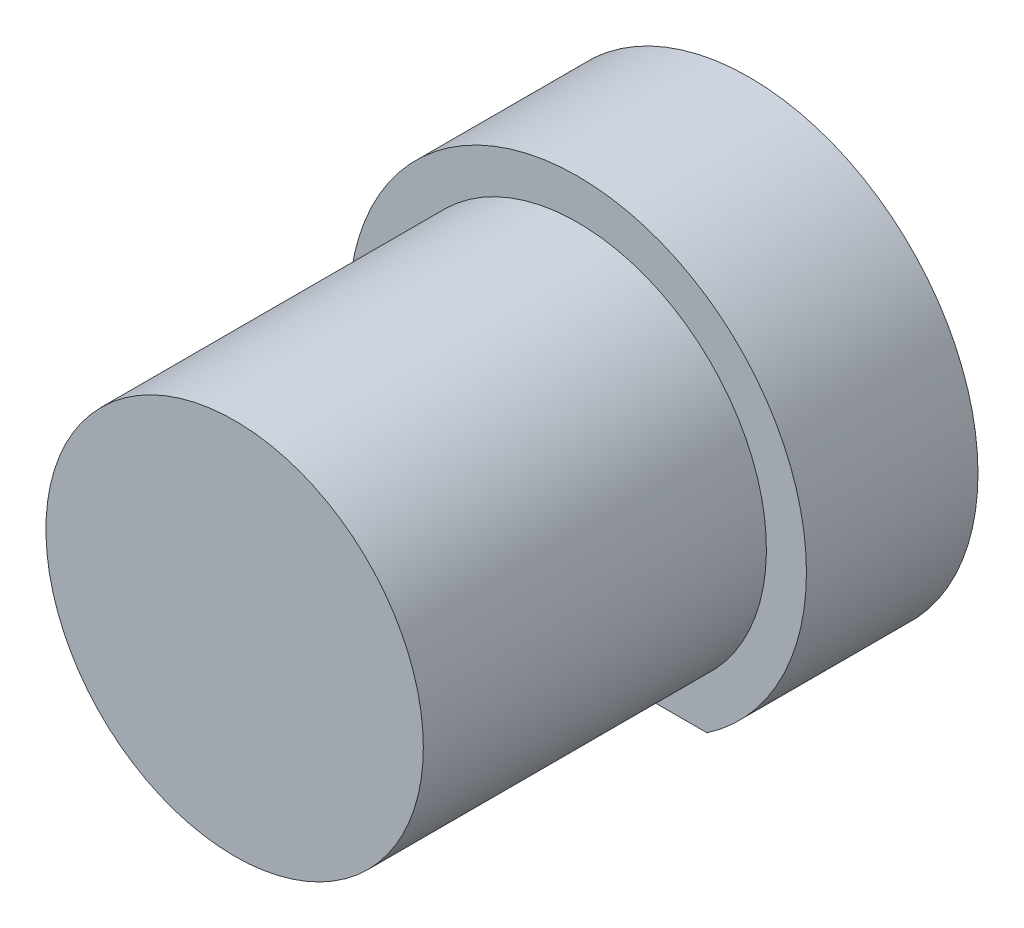
SolidWorks part; units mm, degrees
ref_plane "Front" through (0, 0, 0) normal (0, 0, 1) x (1, 0, 0)
ref_plane "Top" through (0, 0, 0) normal (0, 1, 0) x (1, 0, 0)
ref_plane "Right" through (0, 0, 0) normal (1, 0, 0) x (0, 0, -1)
sketch "Sketch1" plane through (0, 0, 0) normal (0, 0, 1) x (1, 0, 0)
  circle A0 centre (0, 0) radius 2
  dimension "D1" = 4
extrude "Boss-Extrude1" add sketch "Sketch1" along normal blind 1.5
sketch "Sketch2" plane through (0, 0, 1.5) normal (0, 0, 1) x (1, 0, 0)
  circle A0 centre (0, 0) radius 1.65
  dimension "D1" = 3.3
extrude "Boss-Extrude2" add sketch "Sketch2" along normal blind 3
sketch "Sketch3" plane through (0, 0, 1.5) normal (0, 0, 1) x (1, 0, 0)
  line L0 (-1.1303, -1.65) -> (1.1303, -1.65)
  line L1 (0, 0) -> (0, -2) construction
  circle A0 centre (0, 0) radius 2 construction
  circle A1 centre (0, 0) radius 1.65 construction
  arc A2 (-1.1303, -1.65) -> (1.1303, -1.65) centre (0, 0) ccw
  point P6 (0, -1.65)
extrude "Cut-Extrude1" cut sketch "Sketch3" against normal up to surface (1.5 mm away) up to face at (2, 0, 0)
